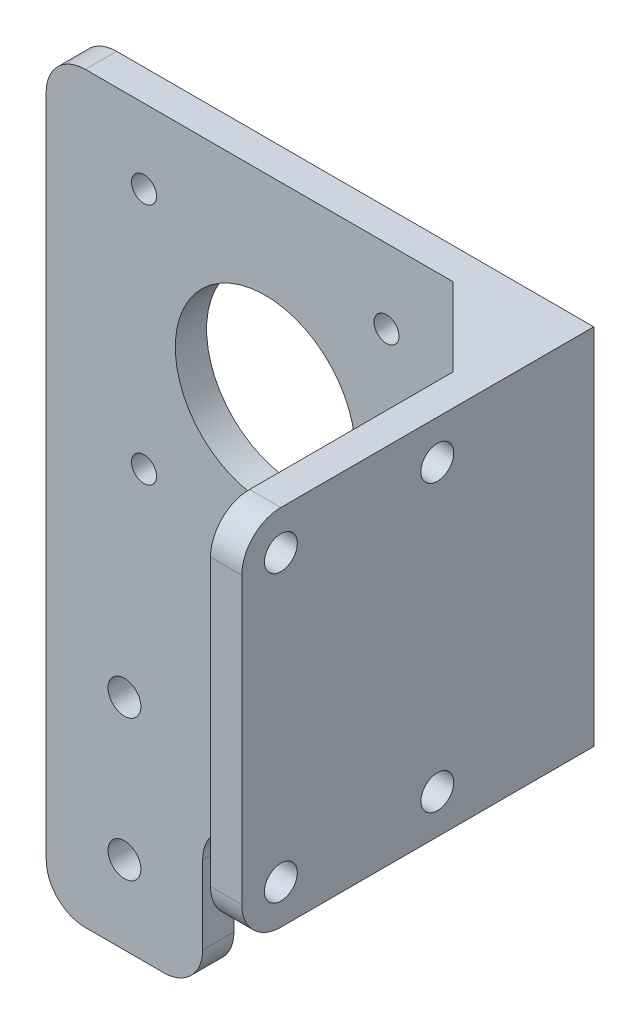
SolidWorks part; units mm, degrees
ref_plane "Спереди" through (0, 0, 0) normal (0, 0, 1) x (1, 0, 0)
ref_plane "Сверху" through (0, 0, 0) normal (0, 1, 0) x (1, 0, 0)
ref_plane "Справа" through (0, 0, 0) normal (1, 0, 0) x (0, 0, -1)
sketch "Model" plane through (0, 0, 0) normal (0, 0, 1) x (1, 0, 0)
  line L69 (274.0282, 189.1642) -> (274.0282, 151.2354)
  line L70 (272.5637, 147.6998) -> (265.4927, 140.6288)
  line L71 (264.0282, 137.0932) -> (264.0282, 124.1643)
  line L72 (259.0282, 119.1644) -> (249.0282, 119.1644)
  line L73 (244.0283, 114.1644) -> (244.0283, 104.1644)
  line L74 (239.0283, 99.1644) -> (229.0283, 99.1644)
  line L75 (224.0283, 104.1644) -> (224.0283, 189.1642)
  line L76 (229.0283, 194.1642) -> (269.0282, 194.1642)
  circle A41 centre (267.5282, 184.6642) radius 1.6
  circle A42 centre (267.5282, 153.6643) radius 1.6
  circle A43 centre (236.5283, 153.6643) radius 1.6
  circle A44 centre (236.5283, 184.6642) radius 1.6
  circle A45 centre (254.0282, 127.1643) radius 2.1
  circle A46 centre (234.0283, 127.1643) radius 2.1
  circle A47 centre (234.0283, 109.1644) radius 2.1
  circle A48 centre (252.0282, 169.1643) radius 11.5
  arc A150 (272.5637, 147.6998) -> (274.0282, 151.2354) centre (269.0282, 151.2354) ccw
  arc A151 (265.4927, 140.6288) -> (264.0282, 137.0932) centre (269.0282, 137.0932) ccw
  arc A152 (259.0282, 119.1644) -> (264.0282, 124.1643) centre (259.0282, 124.1643) ccw
  arc A153 (249.0282, 119.1644) -> (244.0283, 114.1644) centre (249.0282, 114.1644) ccw
  arc A154 (239.0283, 99.1644) -> (244.0283, 104.1644) centre (239.0283, 104.1644) ccw
  arc A155 (224.0283, 104.1644) -> (229.0283, 99.1644) centre (229.0283, 104.1644) ccw
  arc A156 (229.0283, 194.1642) -> (224.0283, 189.1642) centre (229.0283, 189.1642) ccw
  arc A157 (274.0282, 189.1642) -> (269.0282, 194.1642) centre (269.0282, 189.1642) ccw
  dimension "D1" = 5
extrude "Бобышка-Вытянуть1" add sketch "Model" along normal blind 4
sketch "Эскиз1" plane through (0, 0, 0) normal (0, 0, -1) x (-1, 0, 0)
  line L0 (-269.0282, 194.1642) -> (-274.0282, 194.1642) construction
  line L1 (-274.0282, 194.1642) -> (-274.0282, 147.6998) construction
  line L2 (-274.0282, 147.6998) -> (-272.5637, 147.6998) construction
  line L4 (-274.0282, 194.1642) -> (-286.0282, 194.1642)
  line L5 (-274.0282, 189.1642) -> (-274.0282, 152.0643)
  line L6 (-274.0282, 147.6998) -> (-286.0282, 147.6998)
  line L7 (-286.0282, 194.1642) -> (-286.0282, 147.6998)
  line L8 (-274.0282, 194.1642) -> (-269.0282, 194.1642)
  line L10 (-274.0282, 189.1642) -> (-269.0282, 189.1642)
  line L11 (-269.0282, 194.1642) -> (-269.0282, 189.1642)
  line L12 (-274.0282, 147.6998) -> (-271.5282, 147.6998)
  line L14 (-274.0282, 152.0643) -> (-271.5282, 152.0643)
  line L15 (-271.5282, 147.6998) -> (-271.5282, 152.0643)
  dimension "D1" = 12
extrude "Бобышка-Вытянуть2" add sketch "Эскиз1" against normal blind 4
fillet "Скругление1" radius 5 1 edges at (272.5637, 147.6998, 2)
sketch "Эскиз2" plane through (286.0282, 0, 0) normal (1, 0, 0) x (0, 0, -1)
  line L0 (-4, 194.1642) -> (0, 194.1642) construction
  line L1 (0, 147.6998) -> (-40, 147.6998)
  line L2 (0, 147.6998) -> (0, 194.1642)
  line L3 (0, 194.1642) -> (-40, 194.1642)
  line L4 (-45, 152.6998) -> (-45, 189.1642)
  arc A0 (-40, 147.6998) -> (-45, 152.6998) centre (-40, 152.6998) cw
  arc A1 (-45, 189.1642) -> (-40, 194.1642) centre (-40, 189.1642) cw
  circle A2 centre (-40, 189.1642) radius 2.1
  circle A3 centre (-40, 152.6998) radius 2.1
  circle A4 centre (-20, 189.1642) radius 2.1
  circle A5 centre (-20, 152.6998) radius 2.1
  point P11 (-45, 194.1642)
  dimension "D2" = 5
  dimension "D3" = 4.2
  dimension "D4" = 4.2
  dimension "D1" = 45
  dimension "D5" = 2
extrude "Бобышка-Вытянуть3" add sketch "Эскиз2" along normal blind 4
sketch "Эскиз3" plane through (0, 194.1642, 0) normal (0, 1, 0) x (1, 0, 0)
  line L0 (286.0282, -4) -> (276.0282, -4)
  line L1 (286.0282, -4) -> (229.0283, -4) construction
  line L2 (276.0282, -4) -> (286.0282, -14)
  line L3 (286.0282, -4) -> (286.0282, -40) construction
  line L4 (286.0282, -14) -> (286.0282, -4)
  dimension "D1" = 10
  dimension "D2" = 10
extrude "Бобышка-Вытянуть4" add sketch "Эскиз3" against normal blind 4
ref_plane "Плоскость1" through (0, 170.932, 0) normal (0, 1, 0) x (1, 0, 0)
mirror "Зеркальное отражение1" about plane through (0, 170.932, 0) normal (0, 1, 0) of "Бобышка-Вытянуть4"
